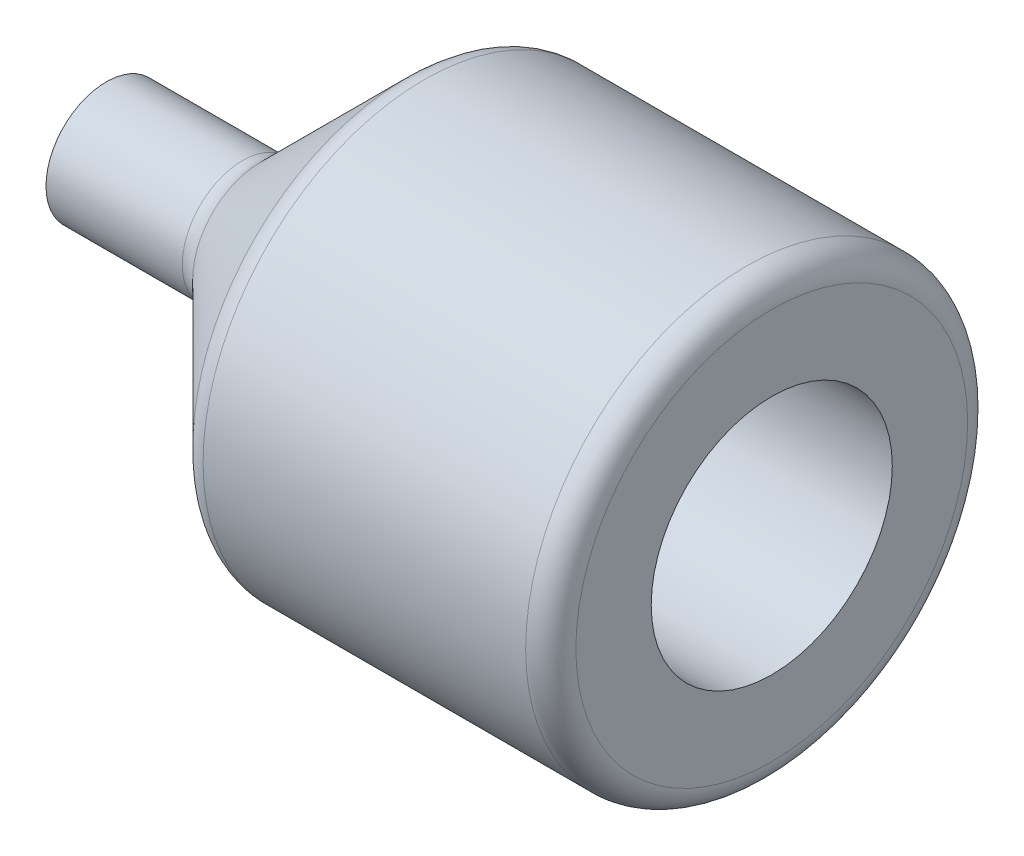
SolidWorks part; units mm, degrees
ref_plane "Front Plane" through (0, 0, 0) normal (0, 0, 1) x (1, 0, 0)
ref_plane "Top Plane" through (0, 0, 0) normal (0, 1, 0) x (1, 0, 0)
ref_plane "Right Plane" through (0, 0, 0) normal (1, 0, 0) x (0, 0, -1)
sketch "Sketch1" plane through (0, 0, 84.279) normal (0, 0, 1) x (1, 0, 0)
  line L0 (-88.572, 107.621) -> (-96.272, 107.621)
  line L1 (-96.272, 107.621) -> (-101.072, 102.821)
  line L2 (-101.072, 102.821) -> (-115.072, 102.821)
  line L3 (-115.072, 102.821) -> (-115.072, 105.221)
  line L5 (-109.2306, 105.221) -> (-102.8306, 111.621)
  line L6 (-102.8306, 111.621) -> (-88.572, 111.621)
  line L7 (-88.572, 111.621) -> (-88.572, 107.621)
  line L9 (-86.072, 113.821) -> (-86.072, 91.821) construction
  line L10 (-86.072, 107.621) -> (-96.072, 107.621) construction
  line L11 (-109.272, 105.321) -> (-111.5241, 105.321) construction
  line L12 (-108.772, 105.821) -> (-109.272, 105.321) construction
  line L13 (-86.072, 113.821) -> (-86.072, 91.821)
  line L14 (-86.072, 107.621) -> (-96.072, 107.621)
  line L15 (-109.272, 105.321) -> (-111.5241, 105.321)
  line L16 (-108.772, 105.821) -> (-109.272, 105.321)
  line L17 (-115.072, 105.221) -> (-109.2306, 105.221)
  line L18 (-96.072, 107.621) -> (-96.072, 98.021) construction
  line L19 (-96.072, 107.621) -> (-96.072, 98.021)
  line L20 (-96.072, 102.821) -> (-106.9914, 102.821) construction
  dimension "D1" = 0.1
  dimension "D2" = 0.1
  dimension "D3" = 4
  dimension "2.5" = 2.5
  dimension "D4" = 5
  dimension "D5" = 19
ref_axis "Axis1" through (-96.072, 102.821, 84.279) along (1, 0, 0)
revolve "Revolve3" add sketch "Sketch1" angle 360 about axis through (-96.072, 102.821, 84.279) along (1, 0, 0)
fillet "Fillet1" radius 1 3 edges at (-109.2306, 102.821, 86.679) (-88.572, 102.821, 93.079) (-102.8306, 102.821, 93.079)
